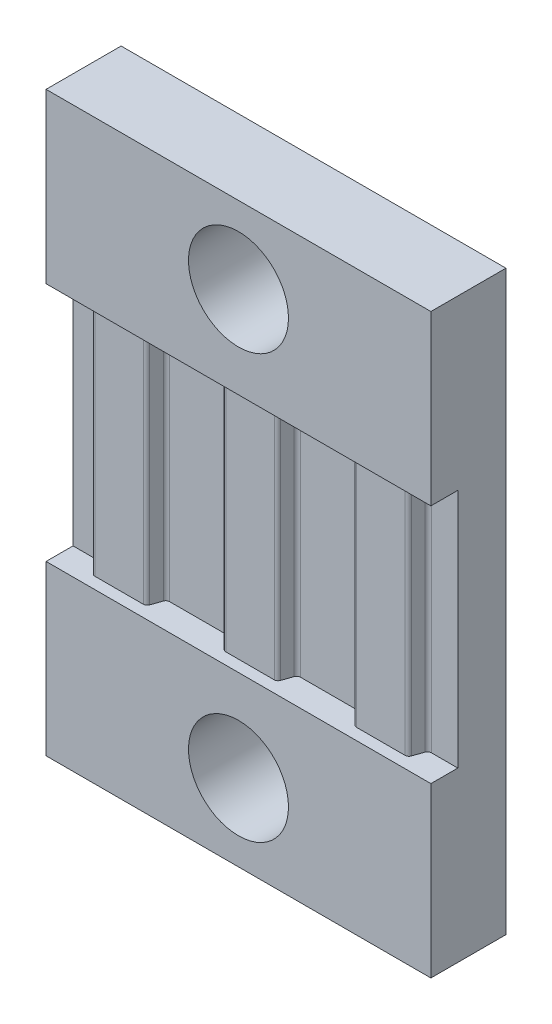
SolidWorks part; units mm, degrees
ref_plane "Front Plane" through (0, 0, 0) normal (0, 0, 1) x (1, 0, 0)
ref_plane "Top Plane" through (0, 0, 0) normal (0, 1, 0) x (1, 0, 0)
ref_plane "Right Plane" through (0, 0, 0) normal (1, 0, 0) x (0, 0, -1)
sketch "Sketch1" plane through (0, 0, 0) normal (0, 0, 1) x (1, 0, 0)
  line L0 (-6.35, 0) -> (6.35, 0) construction
  line L1 (-6.35, -9.525) -> (6.35, -9.525)
  line L2 (-6.35, -9.525) -> (-6.35, 9.525)
  line L3 (-6.35, 9.525) -> (6.35, 9.525)
  line L4 (6.35, -9.525) -> (6.35, 9.525)
  line L5 (-6.35, -9.525) -> (6.35, 9.525) construction
  line L6 (-6.35, 9.525) -> (6.35, -9.525) construction
  circle A0 centre (0, 6.985) radius 1.65
  circle A1 centre (0, -6.985) radius 1.65
  point P0 (0, 0)
  point P10 (0, 0)
  dimension "D3" = 3.3
  dimension "D1" = 19.05
  dimension "D2" = 12.7
  dimension "D4" = 2.54
extrude "Boss-Extrude1" add sketch "Sketch1" along normal blind 1.5875
sketch "Sketch2" plane through (0, 0, 1.5875) normal (0, 0, 1) x (1, 0, 0)
  line L0 (-6.35, 0) -> (6.35, 0) construction
  line L1 (-6.35, 9.525) -> (-6.35, -9.525) construction
  line L2 (6.35, -9.525) -> (6.35, 9.525) construction
  line L3 (-6.35, -3.9688) -> (6.35, -3.9688)
  line L4 (-6.35, 9.525) -> (6.35, 9.525)
  line L5 (-6.35, 9.525) -> (-6.35, 3.9688)
  line L6 (-6.35, 3.9688) -> (6.35, 3.9688)
  line L7 (6.35, 9.525) -> (6.35, 3.9688)
  line L8 (6.35, -9.525) -> (6.35, -3.9688)
  line L9 (-6.35, -9.525) -> (6.35, -9.525)
  line L10 (-6.35, -9.525) -> (-6.35, -3.9688)
  circle A0 centre (0, -6.985) radius 1.65 construction
  circle A1 centre (0, 6.985) radius 1.65 construction
  circle A2 centre (0, -6.985) radius 1.65
  circle A3 centre (0, 6.985) radius 1.65
  dimension "D1" = 7.9375
extrude "Boss-Extrude2" add sketch "Sketch2" along normal blind 0.889
sketch "Sketch3" plane through (0, 3.9688, 0) normal (0, -1, 0) x (1, 0, 0)
  line L0 (-6.35, 1.5875) -> (6.35, 1.5875) construction
  line L1 (0, 1.5875) -> (0, 2.0955) construction
  line L2 (-0.8001, 2.0955) -> (0.8001, 2.0955)
  line L3 (-1.1557, 1.5875) -> (1.1557, 1.5875)
  line L4 (0.9202, 2.0097) -> (1.0356, 1.6733)
  line L5 (-0.9202, 2.0097) -> (-1.0356, 1.6733)
  arc A0 (1.1557, 1.5875) -> (1.0356, 1.6733) centre (1.1557, 1.7145) cw
  arc A1 (0.8001, 2.0955) -> (0.9202, 2.0097) centre (0.8001, 1.9685) cw
  arc A2 (-1.1557, 1.5875) -> (-1.0356, 1.6733) centre (-1.1557, 1.7145) ccw
  arc A3 (-0.8001, 2.0955) -> (-0.9202, 2.0097) centre (-0.8001, 1.9685) ccw
  dimension "D2" = 0.127
  dimension "D3" = 0.127
  dimension "D1" = 0.508
  dimension "D4" = 0.3556
  dimension "D5" = 1.6002
extrude "Boss-Extrude3" add sketch "Sketch3" along normal up to next
pattern_linear "LPattern1" count 2 spacing 4.318 along (1, 0, 0) count 2 spacing 4.318 along (-1, 0, 0) of "Boss-Extrude3"
